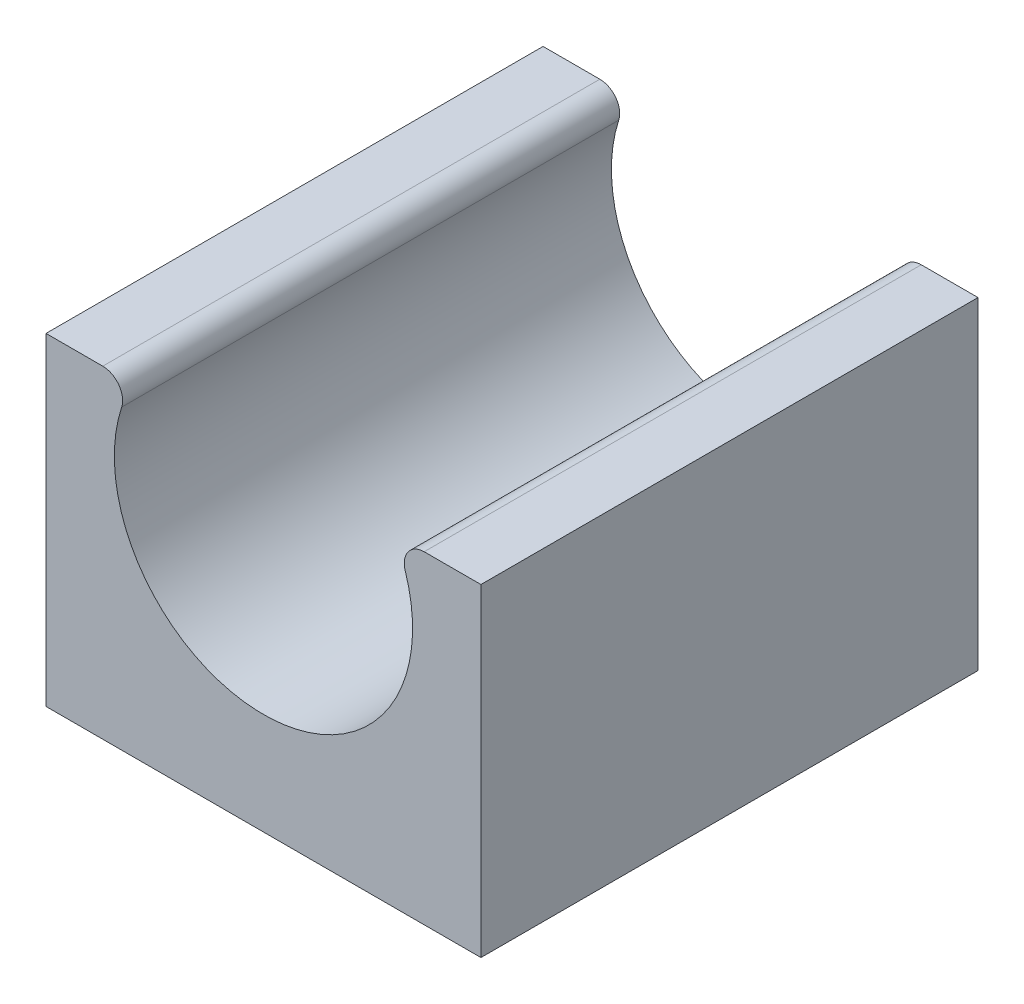
SolidWorks part; units mm, degrees
ref_plane "Front Plane" through (0, 0, 0) normal (0, 0, 1) x (1, 0, 0)
ref_plane "Top Plane" through (0, 0, 0) normal (0, 1, 0) x (1, 0, 0)
ref_plane "Right Plane" through (0, 0, 0) normal (1, 0, 0) x (0, 0, -1)
sketch "Sketch1" plane through (0, 0, 0) normal (0, 0, 1) x (1, 0, 0)
  line L0 (-5.25, 6.5) -> (-8.75, 6.5)
  line L1 (8.75, -6.5) -> (-8.75, -6.5)
  line L2 (8.75, -6.5) -> (8.75, 6.5)
  line L3 (8.75, 6.5) -> (5.25, 6.5)
  line L4 (-8.75, -6.5) -> (-8.75, 6.5)
  line L5 (8.75, -6.5) -> (-8.75, 6.5) construction
  line L6 (8.75, 6.5) -> (-8.75, -6.5) construction
  arc A0 (-5.25, 6.5) -> (5.25, 6.5) centre (0, 3.5953) ccw
  point P0 (0, 0)
  dimension "D1" = 12
  dimension "D2" = 3.5
  dimension "D3" = 17.5
  dimension "D4" = 13
extrude "Boss-Extrude1" add sketch "Sketch1" along normal blind 20
fillet "Fillet1" radius 0.8 2 edges at (5.25, 6.5, 10) (-5.25, 6.5, 10)
